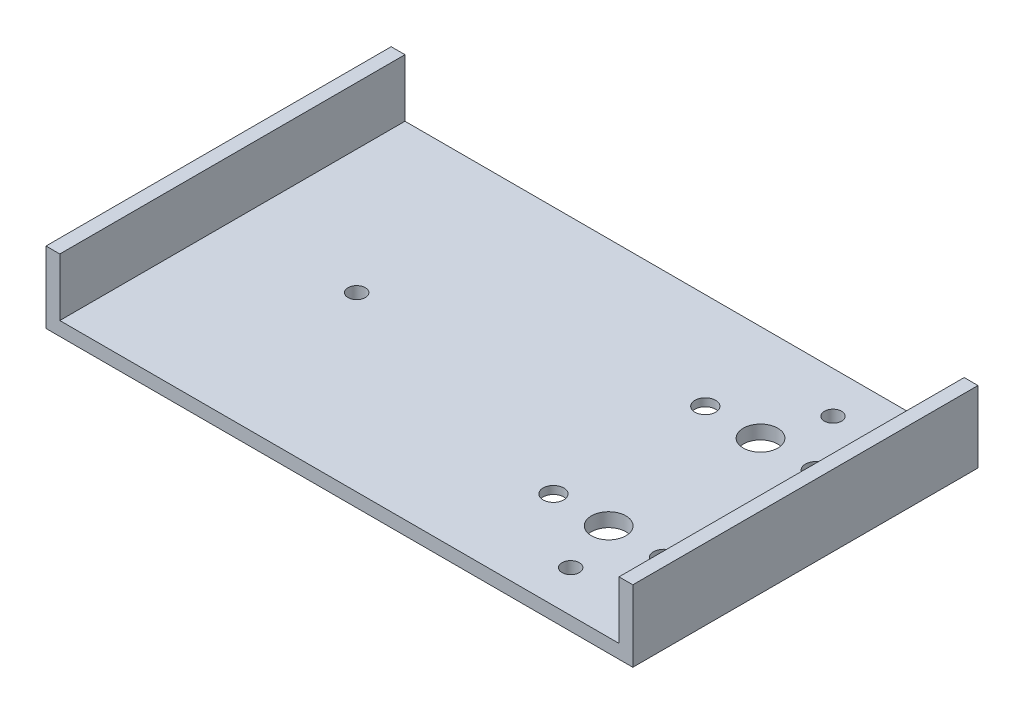
SolidWorks part; units mm, degrees
ref_plane "Спереди" through (0, 0, 0) normal (0, 0, 1) x (1, 0, 0)
ref_plane "Сверху" through (0, 0, 0) normal (0, 1, 0) x (1, 0, 0)
ref_plane "Справа" through (0, 0, 0) normal (1, 0, 0) x (0, 0, -1)
sketch "Эскиз1" plane through (0, 0, 0) normal (0, 0, 1) x (1, 0, 0)
  line L1 (0, 0) -> (170, 0)
  line L3 (4, 4) -> (166, 4)
  line L5 (170, 0) -> (170, 20.7)
  line L6 (0, 0) -> (0, 20.7)
  line L7 (0, 20.7) -> (4, 20.7)
  line L8 (4, 4) -> (4, 20.7)
  line L9 (170, 20.7) -> (166, 20.7)
  line L10 (166, 4) -> (166, 20.7)
  dimension "D1" = 170
  dimension "D2" = 4
  dimension "D3" = 4
  dimension "D4" = 20.7
  dimension "D5" = 4
  dimension "D6" = 20.7
extrude "Бобышка-Вытянуть1" add sketch "Эскиз1" along normal blind 100
sketch "Эскиз2" plane through (0, 0, 0) normal (0, -1, 0) x (1, 0, 0)
  line L0 (135, 100) -> (135, 0) construction
  line L1 (0, 100) -> (170, 100) construction
  line L2 (170, 100) -> (170, 0) construction
  line L3 (170, 50) -> (0, 50) construction
  line L4 (0, 100) -> (0, 0) construction
  line L5 (170, 88) -> (95.8123, 88) construction
  line L6 (170, 12) -> (95.5195, 12) construction
  line L7 (0, 0) -> (170, 0) construction
  line L8 (155.9807, 72) -> (108.093, 72) construction
  line L9 (154.9902, 28) -> (107.2674, 28) construction
  circle A0 centre (135, 72) radius 5
  circle A1 centre (135, 28) radius 5
  circle A2 centre (40, 50) radius 2.5
  circle A3 centre (160, 88) radius 2.5
  circle A4 centre (140, 88) radius 2.5
  circle A5 centre (160, 12) radius 2.5
  circle A6 centre (140, 12) radius 2.5
  circle A7 centre (151, 28) radius 3
  circle A8 centre (119, 28) radius 3
  circle A9 centre (151, 72) radius 3
  circle A10 centre (119, 72) radius 3
  point P44 (121.9247, 27.0962)
  dimension "D2" = 10
  dimension "D3" = 10
  dimension "D6" = 5
  dimension "D8" = 5
  dimension "D9" = 5
  dimension "D14" = 5
  dimension "D15" = 5
  dimension "D18" = 6
  dimension "D19" = 6
  dimension "D20" = 6
  dimension "D21" = 6
  dimension "D1" = 35
  dimension "D4" = 44
  dimension "D5" = 22
  dimension "D7" = 40
  dimension "D10" = 10
  dimension "D11" = 20
  dimension "D12" = 12
  dimension "D13" = 12
  dimension "D16" = 10
  dimension "D17" = 20
  dimension "D22" = 16
  dimension "D23" = 16
  dimension "D24" = 16
  dimension "D25" = 16
extrude "Вырез-Вытянуть1" cut sketch "Эскиз2" against normal blind 4
chamfer "Фаска3" distance 3 angle 30 1 edges at (151, 0, 69)
chamfer "Фаска4" distance 3 angle 30 1 edges at (119, 0, 69)
chamfer "Фаска5" distance 3 angle 30 1 edges at (119, 0, 25)
chamfer "Фаска6" distance 3 angle 30 1 edges at (151, 0, 25)
